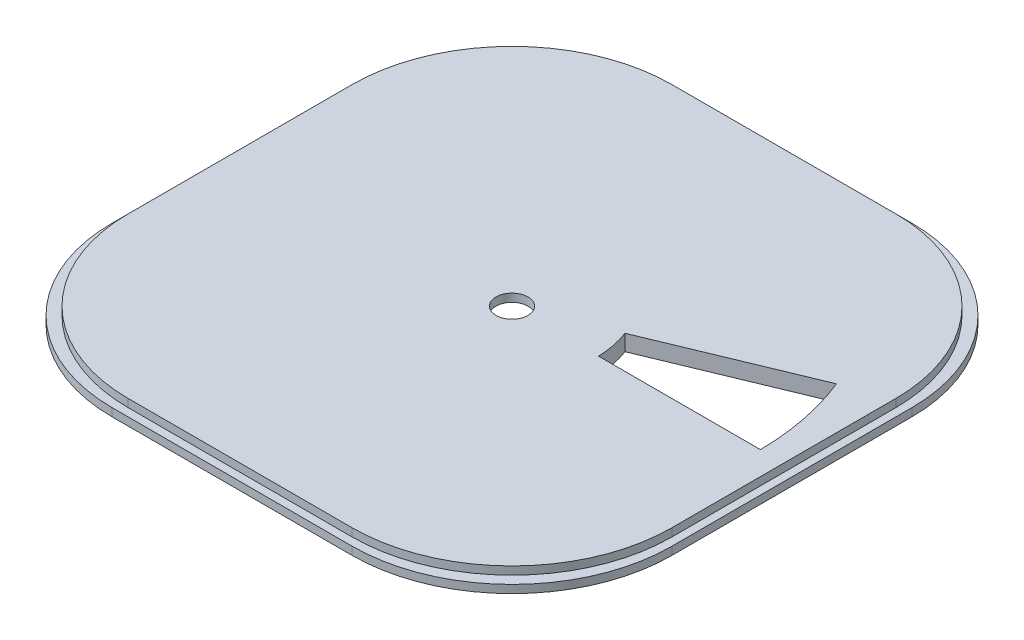
SolidWorks part; units mm, degrees
ref_plane "Front Plane" through (0, 0, 0) normal (0, 0, 1) x (1, 0, 0)
ref_plane "Top Plane" through (0, 0, 0) normal (0, 1, 0) x (1, 0, 0)
ref_plane "Right Plane" through (0, 0, 0) normal (1, 0, 0) x (0, 0, -1)
sketch "Sketch1" plane through (0, 0, 0) normal (0, 1, 0) x (1, 0, 0)
  line L1 (-30, 70) -> (30, 70)
  line L2 (-70, 30) -> (-70, -30)
  line L3 (-30, -70) -> (30, -70)
  line L4 (70, 30) -> (70, -30)
  line L5 (-28, 68) -> (28, 68)
  line L6 (-68, 28) -> (-68, -28)
  line L7 (-28, -68) -> (28, -68)
  line L8 (68, 28) -> (68, -28)
  arc A0 (-30, -70) -> (-70, -30) centre (-30, -30) cw
  arc A1 (30, -70) -> (70, -30) centre (30, -30) ccw
  arc A2 (70, 30) -> (30, 70) centre (30, 30) ccw
  arc A3 (-70, 30) -> (-30, 70) centre (-30, 30) cw
  arc A4 (-68, -28) -> (-28, -68) centre (-28, -28) ccw
  arc A5 (28, -68) -> (68, -28) centre (28, -28) ccw
  arc A6 (68, 28) -> (28, 68) centre (28, 28) ccw
  arc A7 (-68, 28) -> (-28, 68) centre (-28, 28) cw
  dimension "D1" = 40
  dimension "D2" = 40
extrude "Boss-Extrude5" add sketch "Sketch1" against normal blind 2 contours A3 L1 A2 L4 A1 L3 A0 L2
sketch "Sketch5" plane through (0, 0, 0) normal (0, 1, 0) x (1, 0, 0)
  line L1 (-28, 68) -> (28, 68)
  line L2 (-68, 28) -> (-68, -28)
  line L3 (-28, -68) -> (28, -68)
  line L4 (68, 28) -> (68, -28)
  arc A0 (-68, -28) -> (-28, -68) centre (-28, -28) ccw
  arc A1 (28, -68) -> (68, -28) centre (28, -28) ccw
  arc A2 (68, 28) -> (28, 68) centre (28, 28) ccw
  arc A3 (-68, 28) -> (-28, 68) centre (-28, 28) cw
  dimension "D1" = 40
extrude "Boss-Extrude6" add sketch "Sketch5" along normal blind 2
sketch "Sketch6" plane through (0, -2, 0) normal (0, -1, 0) x (1, 0, 0)
  circle A0 centre (0, 0) radius 11
extrude "Cut-Extrude1" cut sketch "Sketch6" against normal blind 2
sketch "Sketch7" plane through (0, 0, 0) normal (0, -1, 0) x (1, 0, 0)
  circle A0 centre (0, 0) radius 2.6037
extrude "Cut-Extrude3" cut sketch "Sketch7" against normal blind 35 and the other way blind 24 contours A0
sketch "Sketch8" plane through (0, 0, 0) normal (0, 1, 0) x (1, 0, 0)
  circle A0 centre (13, 13) radius 1.4
  circle A1 centre (13, -13) radius 1.4
  circle A2 centre (-13, -13) radius 1.4
  circle A3 centre (-13, 13) radius 1.4
extrude "Boss-Extrude8" add sketch "Sketch8" against normal blind 4
sketch "Sketch15" plane through (0, 2, 0) normal (0, 1, 0) x (1, 0, 0)
  line L0 (20.0029, 8.2609) -> (57.4252, 23.7618)
  line L1 (21.6471, -0.0048) -> (62.1527, -0.0048)
  arc A0 (21.6471, -0.0048) -> (20.0029, 8.2609) centre (-3.3438, -0.6794) ccw
  arc A1 (62.1527, -0.0048) -> (57.4252, 23.7618) centre (-3.3438, -0.6794) ccw
extrude "Cut-Extrude8" cut sketch "Sketch15" against normal blind 4
sketch "Sketch17" plane through (0, -4, 0) normal (0, -1, 0) x (1, 0, 0)
  circle A4 centre (13, 13) radius 1.4
  circle A5 centre (13, -13) radius 1.4
  circle A6 centre (-13, -13) radius 1.4
  circle A7 centre (-13, 13) radius 1.4
extrude "Cut-Extrude9" cut sketch "Sketch17" against normal blind 2
sketch "Sketch18" plane through (0, -2, 0) normal (0, -1, 0) x (1, 0, 0)
  line L1 (-70, -30) -> (-70, 30) construction
  line L2 (-70, 0) -> (-70, 4)
  line L3 (-70, 4) -> (-10.247, 4)
  line L4 (-70, 0) -> (-70, -4)
  line L5 (-70, -4) -> (-10.247, -4)
  circle A0 centre (0, 0) radius 11 construction
  circle A1 centre (0, 0) radius 11 construction
  arc A2 (-10.247, 4) -> (-10.247, -4) centre (0, 0) ccw
extrude "Cut-Extrude10" cut sketch "Sketch18" against normal blind 1
sketch "Sketch19" plane through (0, 0, 0) normal (0, -1, 0) x (1, 0, 0)
  circle A0 centre (0, 0) radius 4
extrude "Cut-Extrude11" cut sketch "Sketch19" against normal blind 10
